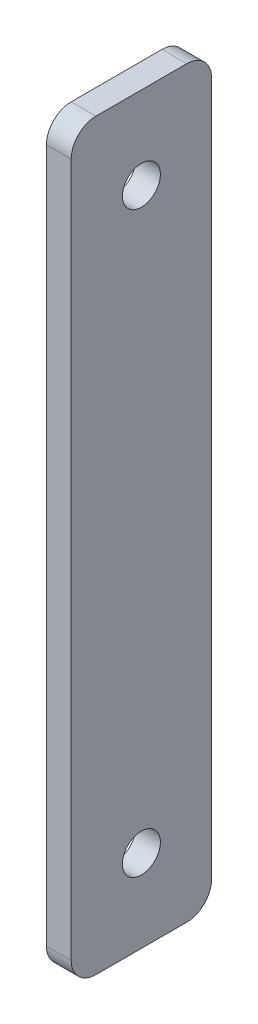
SolidWorks part; units mm, degrees
ref_plane "Спереди" through (0, 0, 0) normal (0, 0, 1) x (1, 0, 0)
ref_plane "Сверху" through (0, 0, 0) normal (0, 1, 0) x (1, 0, 0)
ref_plane "Справа" through (0, 0, 0) normal (1, 0, 0) x (0, 0, -1)
sketch "Sketch1" plane through (0, 0, 0) normal (1, 0, 0) x (0, 0, -1)
  line L0 (-5.5, 0) -> (5.5, 0)
  line L1 (8.5, 3) -> (8.5, 87)
  line L2 (5.5, 90) -> (-5.5, 90)
  line L3 (0, 0) -> (0, 90) construction
  line L4 (-8.5, 3) -> (-8.5, 87)
  line L5 (-8.5, 45) -> (8.5, 45) construction
  arc A0 (8.5, 87) -> (5.5, 90) centre (5.5, 87) ccw
  arc A1 (5.5, 0) -> (8.5, 3) centre (5.5, 3) ccw
  arc A2 (-5.5, 0) -> (-8.5, 3) centre (-5.5, 3) cw
  arc A3 (-8.5, 87) -> (-5.5, 90) centre (-5.5, 87) cw
  circle A4 centre (0, 10) radius 2.3
  circle A5 centre (0, 80) radius 2.3
  dimension "D1" = 3
  dimension "D4" = 4.6
  dimension "D2" = 17
  dimension "D3" = 90
  dimension "D5" = 10
extrude "Boss-Extrude1" add sketch "Sketch1" along normal blind 3
